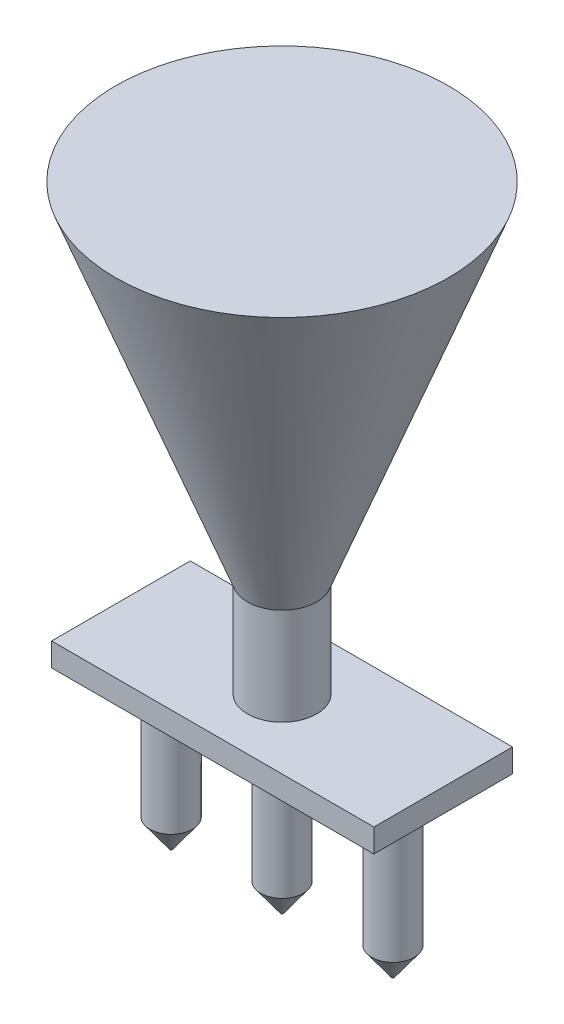
SolidWorks part; units mm, degrees
ref_plane "Front Plane" through (0, 0, 0) normal (0, 0, 1) x (1, 0, 0)
ref_plane "Top Plane" through (0, 0, 0) normal (0, 1, 0) x (1, 0, 0)
ref_plane "Right Plane" through (0, 0, 0) normal (1, 0, 0) x (0, 0, -1)
sketch "Sketch1" plane through (0, 0, 0) normal (0, 0, 1) x (1, 0, 0)
  line L1 (-116.2386, 8.429) -> (116.2386, 8.429)
  line L2 (-116.2386, 8.429) -> (-116.2386, -8.429)
  line L3 (-116.2386, -8.429) -> (116.2386, -8.429)
  line L4 (116.2386, 8.429) -> (116.2386, -8.429)
  line L5 (-116.2386, 8.429) -> (116.2386, -8.429) construction
  line L6 (-116.2386, -8.429) -> (116.2386, 8.429) construction
  point P0 (0, 0)
extrude "Boss-Extrude1" add sketch "Sketch1" along normal blind 100
sketch "Sketch2" plane through (0, 8.429, 0) normal (0, 1, 0) x (1, 0, 0)
  line L0 (-116.2386, -50) -> (116.2386, -50) construction
  line L1 (-116.2386, -100) -> (-116.2386, 0) construction
  line L2 (116.2386, -100) -> (116.2386, 0) construction
  line L3 (0, 0) -> (0, -100) construction
  line L4 (116.2386, -100) -> (-116.2386, -100) construction
  circle A0 centre (0, -50) radius 25
  dimension "D1" = 50
extrude "Boss-Extrude2" add sketch "Sketch2" along normal blind 70
sketch "Sketch5" plane through (0, -8.429, 0) normal (0, -1, 0) x (1, 0, 0)
  line L0 (0, 0) -> (0, 100) construction
  line L1 (-116.2386, 100) -> (116.2386, 100) construction
  circle A0 centre (0, 50) radius 20
  dimension "D1" = 40
extrude "Boss-Extrude3" add sketch "Sketch5" along normal blind 20 draft 13
sketch "Sketch6" plane through (0, -28.429, 0) normal (0, -1, 0) x (1, 0, 0)
  circle A1 centre (0, 50) radius 15.3826
  circle A2 centre (0, 50) radius 15.3826
  dimension "D1" = 0
extrude "Boss-Extrude4" add sketch "Sketch6" along normal blind 80
sketch "Sketch7" plane through (0, -108.429, 0) normal (0, -1, 0) x (1, 0, 0)
  circle A1 centre (0, 50) radius 15.3826
  circle A2 centre (0, 50) radius 15.3826
  dimension "D1" = 0
extrude "Boss-Extrude5" add sketch "Sketch7" along normal blind 20 draft 36
pattern_linear "LPattern1" count 2 spacing 80 along (1, 0, 0) of "Boss-Extrude3", "Boss-Extrude5", "Boss-Extrude4"
pattern_linear "LPattern2" count 2 spacing 80 along (-1, 0, 0) of "Boss-Extrude4", "Boss-Extrude3", "Boss-Extrude5"
ref_plane "Plane2" through (0, 328.429, 0) normal (0, 1, 0) x (1, 0, 0)
sketch "Sketch9" plane through (0, 328.429, 0) normal (0, 1, 0) x (1, 0, 0)
  circle A2 centre (0, -50) radius 120
  dimension "D1" = 240
extrude "Boss-Extrude6" add sketch "Sketch9" against normal blind 250 draft 20.8
